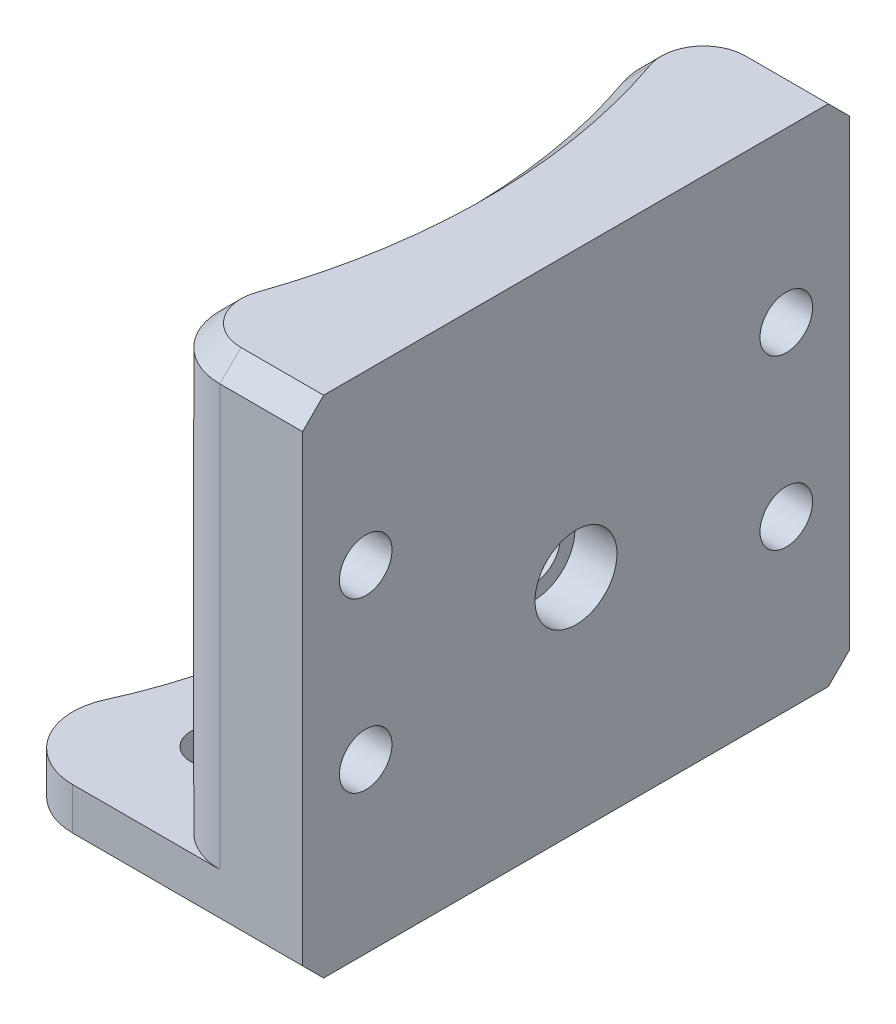
SolidWorks part; units mm, degrees
ref_plane "Спереди" through (0, 0, 0) normal (0, 0, 1) x (1, 0, 0)
ref_plane "Сверху" through (0, 0, 0) normal (0, 1, 0) x (1, 0, 0)
ref_plane "Справа" through (0, 0, 0) normal (1, 0, 0) x (0, 0, -1)
sketch "Эскиз1" plane through (0, 0, 0) normal (0, 1, 0) x (1, 0, 0)
  line L0 (23.6854, 8) -> (23.6854, -8) construction
  line L1 (16.4924, 13) -> (32.75, 13)
  line L2 (16.4924, 13) -> (16.4924, -13) construction
  line L3 (16.4924, -13) -> (32.75, -13)
  line L4 (32.75, 13) -> (32.75, -13)
  circle A0 centre (0, 0) radius 25 construction
  circle A2 centre (0, 0) radius 21
  circle A3 centre (23.6854, 8) radius 1.25
  circle A4 centre (23.6854, -8) radius 1.25
  dimension "D1" = 50
  dimension "D6" = 2.5
  dimension "D7" = 2.5
  dimension "D2" = 4
  dimension "D3" = 26
  dimension "D4" = 32.75
  dimension "D5" = 16
extrude "Бобышка-Вытянуть1" add sketch "Эскиз1" along normal blind 24 contours A2 L3 L4 L1 A4 A3
sketch "Эскиз2" plane through (0, 24, 0) normal (0, 1, 0) x (1, 0, 0)
  circle A0 centre (0, 0) radius 25 construction
  circle A1 centre (0, 0) radius 27.5
  dimension "D1" = 2.5
extrude "Вырез-Вытянуть1" cut sketch "Эскиз2" against normal offset from surface (21 mm away) 3 up to face at (23.6854, 0, 9.25)
fillet "Скругление1" radius 3 4 edges at (24.2332, 13.5, 13) (24.2332, 13.5, -13) (16.4924, 1.5, -13) (16.4924, 1.5, 13)
sketch "Эскиз3" plane through (32.75, 0, 0) normal (1, 0, 0) x (0, 0, -1)
  line L0 (13, 0) -> (-13, 0) construction
  line L1 (-13, 12) -> (13, 12) construction
  line L2 (-10, 16) -> (-10, 8) construction
  line L3 (0, 0) -> (0, 24) construction
  line L4 (13, 24) -> (-13, 24) construction
  line L5 (-13, 24) -> (-13, 0) construction
  line L6 (13, 24) -> (13, 0) construction
  circle A0 centre (0, 10.5) radius 1.25
  circle A2 centre (-10, 16) radius 1.25
  circle A3 centre (-10, 8) radius 1.25
  circle A4 centre (10, 8) radius 1.25
  circle A5 centre (10, 16) radius 1.25
  point P4 (0, 0)
  point P17 (-13, 12)
  dimension "D1" = 2.5
  dimension "D3" = 2.5
  dimension "D2" = 10.5
  dimension "D4" = 8
  dimension "D5" = 20
extrude "Вырез-Вытянуть2" cut sketch "Эскиз3" against normal through all
chamfer "Фаска2" distance 1 angle 45 10 edges at (30.782, 24, -13) (26.3696, 24, -11.7391) (27.5, 24, 0) (30.782, 24, 13) (26.3696, 24, 11.7391) (27.2837, 0, -13) (19.2925, 0, -11.6202) (21, 0, 0) (19.2925, 0, 11.6202) (27.2837, 0, 13)
sketch "Эскиз4" plane through (0, 0, 0) normal (1, 0, 0) x (0, 0, -1)
  line L0 (-13, 12) -> (13, 12) construction
  line L1 (-7.85, 14.7587) -> (-7.85, 17.2413)
  line L2 (-7.85, 17.2413) -> (-10, 18.4826)
  line L3 (-10, 18.4826) -> (-12.15, 17.2413)
  line L4 (-12.15, 17.2413) -> (-12.15, 14.7587)
  line L5 (-12.15, 14.7587) -> (-10, 13.5174)
  line L6 (-10, 13.5174) -> (-7.85, 14.7587)
  line L7 (-13, 23) -> (-13, 1) construction
  line L8 (13, 23) -> (13, 1) construction
  line L9 (0, 24) -> (0, 0) construction
  line L10 (12, 24) -> (-12, 24) construction
  line L11 (12, 0) -> (-12, 0) construction
  line L12 (-10, 10.4826) -> (-7.85, 9.2413)
  line L13 (-12.15, 9.2413) -> (-10, 10.4826)
  line L14 (-12.15, 6.7587) -> (-12.15, 9.2413)
  line L15 (-10, 5.5174) -> (-12.15, 6.7587)
  line L16 (-7.85, 6.7587) -> (-10, 5.5174)
  line L17 (-7.85, 9.2413) -> (-7.85, 6.7587)
  line L18 (7.85, 9.2413) -> (7.85, 6.7587)
  line L19 (7.85, 6.7587) -> (10, 5.5174)
  line L20 (10, 5.5174) -> (12.15, 6.7587)
  line L21 (12.15, 6.7587) -> (12.15, 9.2413)
  line L22 (12.15, 9.2413) -> (10, 10.4826)
  line L23 (10, 10.4826) -> (7.85, 9.2413)
  line L24 (10, 13.5174) -> (7.85, 14.7587)
  line L25 (12.15, 14.7587) -> (10, 13.5174)
  line L26 (12.15, 17.2413) -> (12.15, 14.7587)
  line L27 (10, 18.4826) -> (12.15, 17.2413)
  line L28 (7.85, 17.2413) -> (10, 18.4826)
  line L29 (7.85, 14.7587) -> (7.85, 17.2413)
  circle A0 centre (-10, 16) radius 2.15 construction
  dimension "D1" = 4.3
extrude "Вырез-Вытянуть3" cut sketch "Эскиз4" along normal offset from surface (29.75 mm away) 3 up to face at (32.75, 16, -8.75)
sketch "Эскиз5" plane through (32.75, 0, 0) normal (1, 0, 0) x (0, 0, -1)
  circle A0 centre (0, 10.5) radius 1.95
  dimension "D1" = 3.9
extrude "Вырез-Вытянуть4" cut sketch "Эскиз5" against normal blind 2
sketch "Эскиз6" plane through (0, 0, 0) normal (0, -1, 0) x (1, 0, 0)
  circle A0 centre (23.6854, 8) radius 1.95
  circle A1 centre (23.6854, -8) radius 1.95
  dimension "D1" = 3.9
  dimension "D2" = 3.9
extrude "Вырез-Вытянуть5" cut sketch "Эскиз6" against normal blind 1
equation "\"motor_diameter\"= 30"
equation "\"mm_diameter\"= IIF ( \"motor_diameter\" < 34 , 41 , \"motor_diameter\" + 8 )"
equation "\"upper_shafts_diameter\"= 5"
equation "\"upper_shats_length\"= 180"
equation "\"upper_bearing_d1\"= 10"
equation "\"upper_bearing_d2\"= 5"
equation "\"upper_bearing_h\"= 15"
equation "\"lower_shafts_diameter\"= 5"
equation "\"lower_shafts_length\"= 180"
equation "\"lower_bearing_d1\"= 10"
equation "\"lower_bearing_d2\"= 5"
equation "\"lower_bearing_h\"= 15"
equation "\"print_offset\"= 0.5"
equation "\"bh_screws_d\"= 2"
equation "\"bh_screws_h\"= 20"
equation "\"bh_screws_hh_d\"= 3.4"
equation "\"bh_screws_hh_h\"= 2"
equation "\"bh_nut_d\"= 3.8"
equation "\"bh_nut_h\"= 2"
equation "\"motor_screws_d\"= 3"
equation "\"motor_screws_h\"= 16"
equation "\"motor_screws_hh_d\"= 5.5"
equation "\"motor_screws_hh_h\"= 3"
equation "\"plate_hole_distance\"= 25.4"
equation "\"plate_screws_d\"= 6.5"
equation "\"shafts_diameter\"= IIF ( \"mm_diameter\" < 42 , 42 + 8 , \"mm_diameter\" + 8 )"
equation "\"central_hole_diameter\"= 8"
equation "\"bh_thikness\"= 4"
equation "\"ends_screws_d\"= 4"
equation "\"ends_screws_h\"= 16"
equation "\"ends_screws_hh_d\"= 6.7"
equation "\"ends_screws_hh_h\"= 4.1"
equation "\"ends_nut_d\"= 6.8"
equation "\"ends_nut_h\"= 3"
equation "\"system_radius\" = ( \"shafts_diameter\" + 12 + \"bh_thikness\" / 2 ) / 2"
equation "\"encoder_distance\"= \"system_radius\" + 4"
equation "\"tape_position\"= \"encoder_distance\" - 2 + 3.9 + 1.7 / 2"
equation "\"D1@Эскиз1\"=\"shafts_diameter\""
equation "\"D2@Эскиз1\"=\"bh_thikness\""
equation "\"D4@Эскиз1\"=\"tape_position\"-6"
equation "\"D6@Эскиз1\"=\"bh_screws_d\"+\"print_offset\""
equation "\"D7@Эскиз1\"=\"D6@Эскиз1\""
equation "\"D1@Бобышка-Вытянуть1\"=\"upper_bearing_h\"+6+3"
equation "\"D1@Эскиз2\"=\"bh_thikness\"/2+\"print_offset\""
equation "\"D1@Эскиз3\"=\"bh_screws_d\"+\"print_offset\""
equation "\"D2@Эскиз3\"=\"upper_bearing_h\"/2+3"
equation "\"D3@Эскиз3\"=\"bh_screws_d\"+\"print_offset\""
equation "\"D1@Эскиз4\"=\"bh_nut_d\"+\"print_offset\""
equation "\"D1@Вырез-Вытянуть3\"=-1+12-8"
equation "\"D1@Эскиз5\"=\"bh_screws_hh_d\"+\"print_offset\""
equation "\"D1@Вырез-Вытянуть4\"=\"bh_screws_hh_h\""
equation "\"D1@Эскиз6\"=\"bh_screws_hh_d\"+\"print_offset\""
equation "\"D2@Эскиз6\"=\"D1@Эскиз6\""
equation "\"ft_sensor_d1\" = 9.8"
equation "\"ft_sensor_d2\"= 24.9"
equation "\"ft_sensor_h\"= 7"
equation "\"carbon_pipe_d\"= 14"
